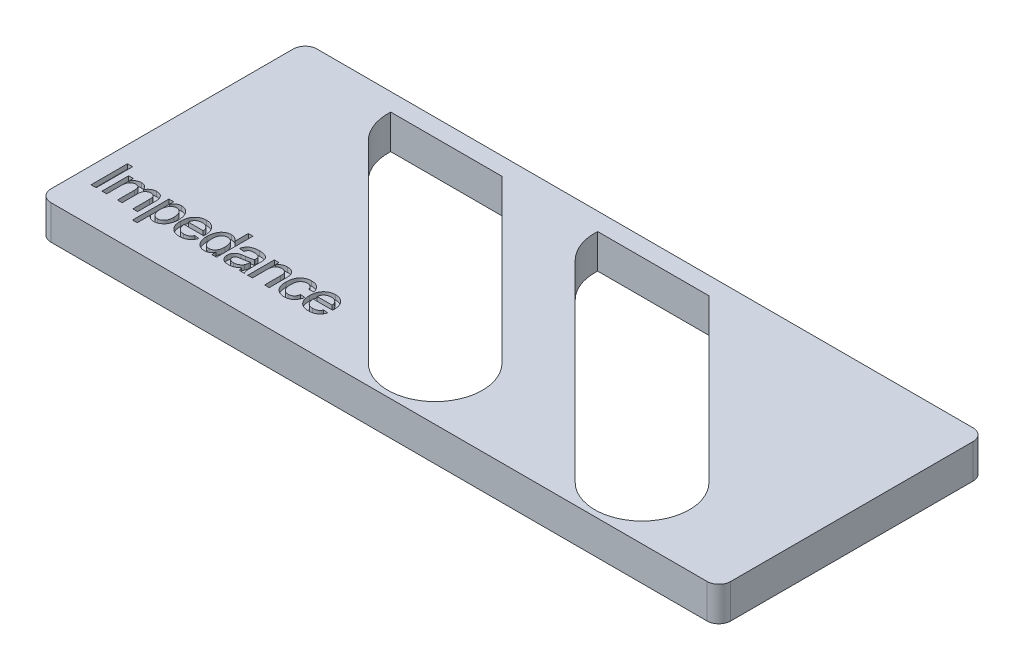
SolidWorks part; units mm, degrees
material "ABS"
ref_plane "Front Plane" through (0, 0, 0) normal (0, 0, 1) x (1, 0, 0)
ref_plane "Top Plane" through (0, 0, 0) normal (0, 1, 0) x (1, 0, 0)
ref_plane "Right Plane" through (0, 0, 0) normal (1, 0, 0) x (0, 0, -1)
sketch "Sketch1" plane through (0, 0, 0) normal (0, 1, 0) x (1, 0, 0)
  line L1 (1, 0) -> (56.5, 0)
  line L2 (0, 1) -> (0, 21.5)
  line L3 (1, 22.5) -> (56.5, 22.5)
  line L4 (57.5, 1) -> (57.5, 21.5)
  arc A0 (56.5, 22.5) -> (57.5, 21.5) centre (56.5, 21.5) cw
  arc A1 (57.5, 1) -> (56.5, 0) centre (56.5, 1) cw
  arc A2 (1, 0) -> (0, 1) centre (1, 1) cw
  arc A3 (0, 21.5) -> (1, 22.5) centre (1, 21.5) cw
  point P11 (0, 0)
  dimension "D1" = 1
extrude "Boss-Extrude1" add sketch "Sketch1" along normal blind 2.9
ref_plane "Plane1" through (0, 3, 0) normal (0, 1, 0) x (1, 0, 0)
sketch "Sketch2" plane through (0, 3, 0) normal (0, 1, 0) x (1, 0, 0)
  line L0 (0, 0) -> (0, 4.5)
  line L1 (0, 21.5) -> (0, 1) construction
  line L2 (0, 4.5) -> (1.5, 4.5)
  line L3 (1.5, 4.5) -> (11.5, 4.5)
  line L4 (29, 4.5) -> (12.7365, 20.7635) construction
  line L7 (29, 4.5) -> (46.5, 4.5)
  line L8 (29, 4.5) -> (12.7365, 20.7635)
  line L9 (46.5, 4.5) -> (30.2365, 20.7635)
  line L10 (46.5, 4.5) -> (30.2365, 20.7635) construction
  line L13 (12.7365, 20.7635) -> (29, 4.5) construction
  line L15 (18.1569, 21) -> (31.8284, 7.3284)
  line L22 (27.2459, 21) -> (34.2426, 21)
  line L23 (15.7426, 21) -> (9.7459, 21)
  line L24 (9.7459, 21) -> (16.7426, 21)
  line L25 (9.9081, 17.935) -> (26.1716, 1.6716)
  line L26 (30.2365, 20.7635) -> (46.5, 4.5) construction
  line L27 (35.6569, 21) -> (49.3284, 7.3284)
  line L28 (27.4081, 17.935) -> (43.6716, 1.6716)
  line L29 (8.7435, 21) -> (18.1569, 21)
  line L30 (26.2435, 21) -> (35.6569, 21)
  arc A4 (8.7435, 21) -> (9.9081, 17.935) centre (12.7365, 20.7635) ccw
  arc A5 (26.1716, 1.6716) -> (31.8284, 7.3284) centre (29, 4.5) ccw
  arc A6 (26.2435, 21) -> (27.4081, 17.935) centre (30.2365, 20.7635) ccw
  arc A7 (43.6716, 1.6716) -> (49.3284, 7.3284) centre (46.5, 4.5) ccw
  point P10 (20.8683, 12.6317)
  point P12 (20.8683, 12.6317)
  point P18 (38.3683, 12.6317)
  point P21 (38.3683, 12.6317)
extrude "Cut-Extrude3" cut sketch "Sketch2" against normal blind 10
sketch "Sketch3" plane through (0, 3, 0) normal (0, 1, 0) x (1, 0, 0)
  text T0 "Impedance" height in points 12
  point P1 (0, 0)
  point P2 (0, 0)
extrude "Cut-Extrude4" cut sketch "Sketch3" against normal blind 0.5
